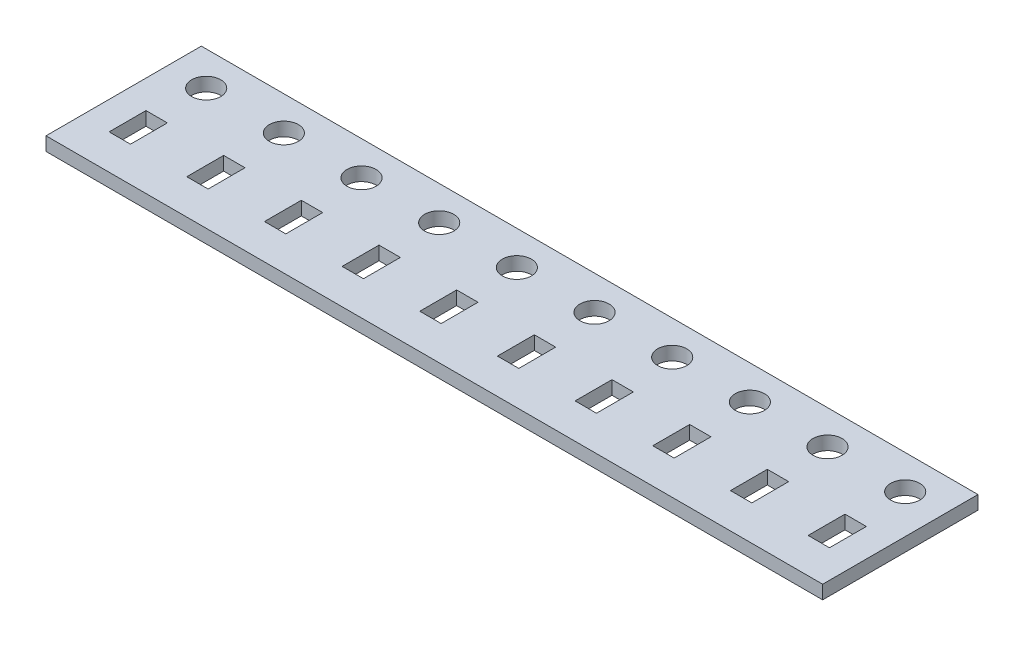
SolidWorks part; units mm, degrees
ref_plane "前视基准面" through (0, 0, 0) normal (0, 0, 1) x (1, 0, 0)
ref_plane "上视基准面" through (0, 0, 0) normal (0, 1, 0) x (1, 0, 0)
ref_plane "右视基准面" through (0, 0, 0) normal (1, 0, 0) x (0, 0, -1)
sketch "草图1" plane through (0, 0, 0) normal (0, 1, 0) x (1, 0, 0)
  line L1 (-2, 8) -> (2, 8)
  line L2 (-2, 8) -> (-2, 0)
  line L3 (-2, 0) -> (2, 0)
  line L4 (2, 8) -> (2, 0)
  line L5 (-2, 8) -> (2, 0) construction
  line L6 (-2, 0) -> (2, 8) construction
  line L7 (-0.55, 3.7) -> (0.55, 3.7)
  line L8 (-0.55, 3.7) -> (-0.55, 1.8)
  line L9 (-0.55, 1.8) -> (0.55, 1.8)
  line L10 (0.55, 3.7) -> (0.55, 1.8)
  line L11 (-0.55, 3.7) -> (0.55, 1.8) construction
  line L12 (-0.55, 1.8) -> (0.55, 3.7) construction
  circle A0 centre (0, 6.25) radius 0.75
  point P4 (0, 4)
  point P5 (0, 0)
  point P9 (0, 0)
  point P14 (0, 2.75)
  dimension "D3" = 1.5
  dimension "D1" = 8
  dimension "D2" = 4
  dimension "D4" = 6.25
  dimension "D5" = 1.1
  dimension "D6" = 1.9
  dimension "D7" = 2.75
extrude "凸台-拉伸1" add sketch "草图1" along normal blind 0.7
sketch "草图2" plane through (0, 0, 0) normal (0, 1, 0) x (1, 0, 0)
  line L0 (0, 0) -> (50000, 0) construction
  line L1 (-2, 0) -> (2, 0) construction
  point P5 (0, 0)
pattern_linear "阵列(线性)2" count 10 spacing 4 along (1, 0, 0) of "凸台-拉伸1"
